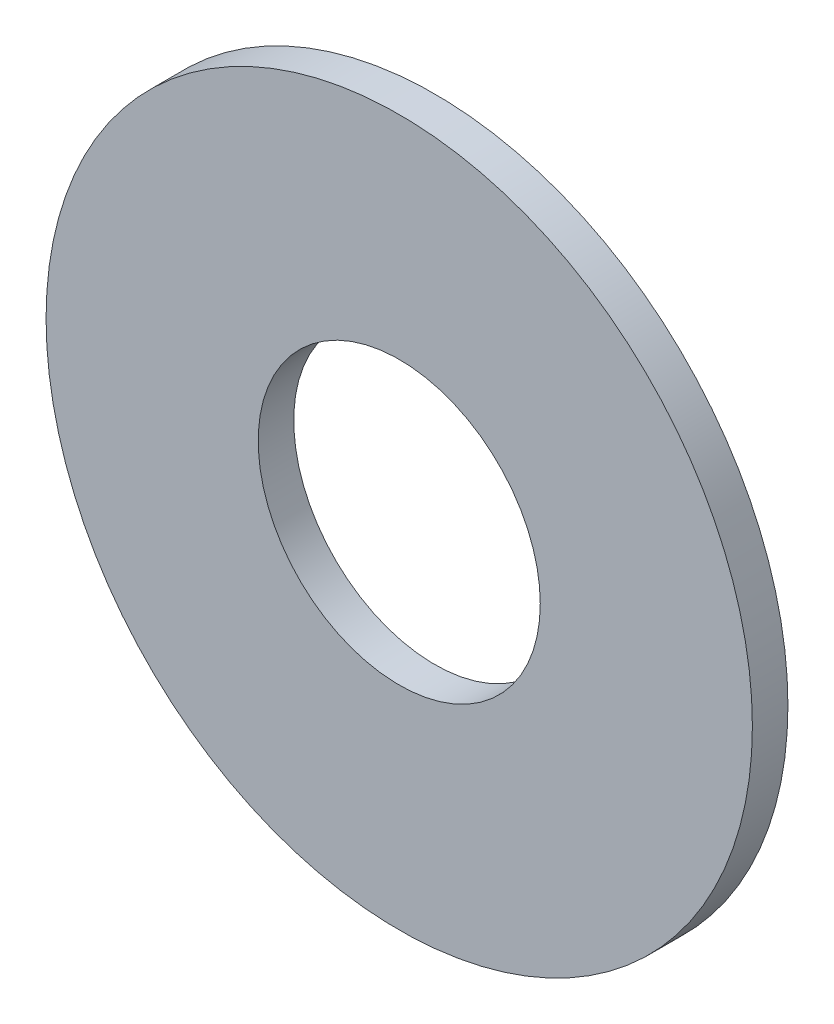
SolidWorks part; units mm, degrees
ref_plane "Front Plane" through (0, 0, 0) normal (0, 0, 1) x (1, 0, 0)
ref_plane "Top Plane" through (0, 0, 0) normal (0, 1, 0) x (1, 0, 0)
ref_plane "Right Plane" through (0, 0, 0) normal (1, 0, 0) x (0, 0, -1)
sketch "Sketch1" plane through (0, 0, 0) normal (0, 0, 1) x (1, 0, 0)
  circle A0 centre (0, 0) radius 1.5875
  circle A1 centre (0, 0) radius 3.975
extrude "Boss-Extrude1" add sketch "Sketch1" along normal blind 0.4
